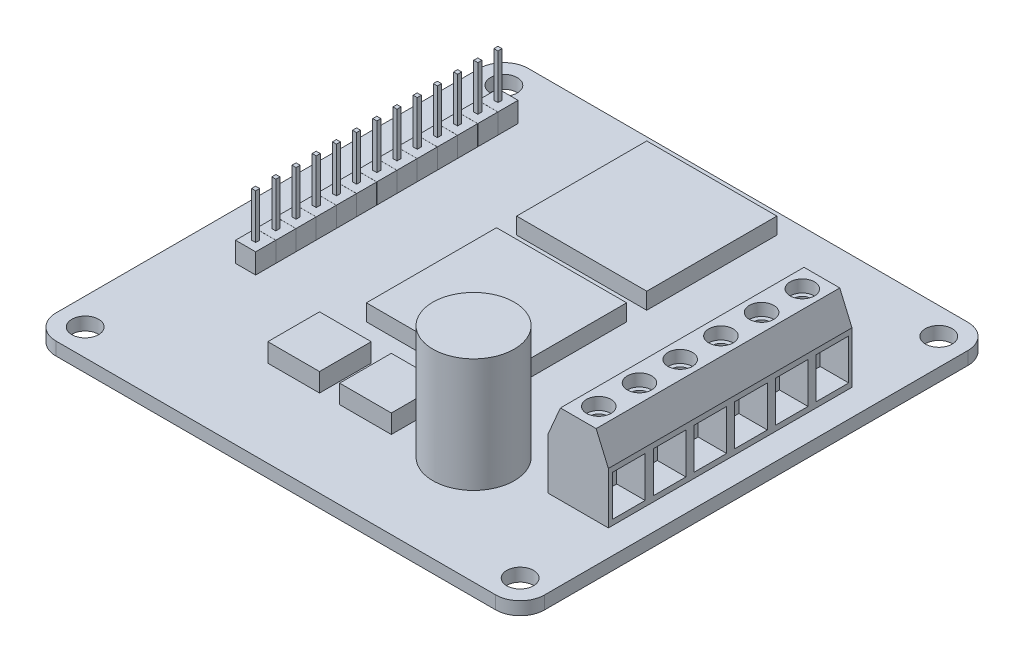
SolidWorks part; units mm, degrees
ref_plane "Front Plane" through (0, 0, 0) normal (0, 0, 1) x (1, 0, 0)
ref_plane "Top Plane" through (0, 0, 0) normal (0, 1, 0) x (1, 0, 0)
ref_plane "Right Plane" through (0, 0, 0) normal (1, 0, 0) x (0, 0, -1)
sketch "Sketch1" plane through (0, 0, 0) normal (0, 1, 0) x (1, 0, 0)
  line L1 (-27, -29) -> (27, -29)
  line L2 (-30, -26) -> (-30, 26)
  line L3 (-27, 29) -> (27, 29)
  line L4 (30, -26) -> (30, 26)
  line L5 (-30, -29) -> (30, 29) construction
  line L6 (-30, 29) -> (30, -29) construction
  arc A0 (-27, -29) -> (-30, -26) centre (-27, -26) cw
  arc A1 (27, -29) -> (30, -26) centre (27, -26) ccw
  arc A2 (27, 29) -> (30, 26) centre (27, 26) cw
  arc A3 (-30, 26) -> (-27, 29) centre (-27, 26) cw
  point P0 (0, 0)
  dimension "D3" = 3
  dimension "D1" = 60
  dimension "D2" = 58
extrude "Boss-Extrude1" add sketch "Sketch1" along normal blind 1.6
sketch "Sketch2" plane through (0, 1.6, 0) normal (0, 1, 0) x (1, 0, 0)
  line L0 (-27, -29) -> (27, -29) construction
  line L1 (30, -26) -> (30, 26) construction
  line L2 (27, 29) -> (-27, 29) construction
  line L3 (-30, 26) -> (-30, -26) construction
  circle A0 centre (-26.71, 25.71) radius 1.645
  circle A1 centre (26.71, 25.71) radius 1.645
  circle A2 centre (-26.71, -25.71) radius 1.645
  circle A3 centre (26.71, -25.71) radius 1.645
  dimension "D1" = 3.29
  dimension "D2" = 3.29
  dimension "D3" = 3.29
  dimension "D4" = 3.29
  dimension "D5" = 3.29
  dimension "D6" = 3.29
  dimension "D7" = 3.29
  dimension "D8" = 3.29
  dimension "D9" = 3.29
  dimension "D10" = 3.29
  dimension "D11" = 3.29
  dimension "D12" = 3.29
extrude "Cut-Extrude1" cut sketch "Sketch2" against normal blind 1.6
sketch "Sketch3" plane through (0, 1.6, 0) normal (0, 1, 0) x (1, 0, 0)
  line L0 (27, 29) -> (-27, 29) construction
  line L1 (-9.9806, 10.55) -> (5.9994, 10.55)
  line L2 (-9.9806, 10.55) -> (-9.9806, 26.53)
  line L3 (-9.9806, 26.53) -> (5.9994, 26.53)
  line L4 (5.9994, 10.55) -> (5.9994, 26.53)
  line L5 (-9.9806, 10.55) -> (5.9994, 26.53) construction
  line L6 (-9.9806, 26.53) -> (5.9994, 10.55) construction
  line L7 (-9.9806, -7.9) -> (5.9994, -7.9)
  line L8 (-9.9806, -7.9) -> (-9.9806, 8.08)
  line L9 (-9.9806, 8.08) -> (5.9994, 8.08)
  line L10 (5.9994, -7.9) -> (5.9994, 8.08)
  line L11 (-9.9806, -7.9) -> (5.9994, 8.08) construction
  line L12 (-9.9806, 8.08) -> (5.9994, -7.9) construction
  point P0 (-1.9906, 18.54)
  point P5 (-1.9906, 0.09)
  dimension "D1" = 15.98
  dimension "D2" = 15.98
  dimension "D3" = 15.98
  dimension "D4" = 15.98
  dimension "D5" = 2.47
  dimension "D6" = 2.47
extrude "Boss-Extrude2" add sketch "Sketch3" along normal blind 2.03
sketch "Sketch4" plane through (0, 1.6, 0) normal (0, 1, 0) x (1, 0, 0)
  line L0 (-9.9806, -7.9) -> (5.9994, -7.9) construction
  line L1 (3.5294, -12) -> (-2.8206, -12)
  line L2 (3.5294, -12) -> (3.5294, -18.35)
  line L3 (3.5294, -18.35) -> (-2.8206, -18.35)
  line L4 (-2.8206, -12) -> (-2.8206, -18.35)
  line L5 (-5.2906, -12) -> (-11.6406, -12)
  line L6 (-5.2906, -12) -> (-5.2906, -18.35)
  line L7 (-5.2906, -18.35) -> (-11.6406, -18.35)
  line L8 (-11.6406, -12) -> (-11.6406, -18.35)
  line L9 (5.9994, -7.9) -> (5.9994, 8.08) construction
  dimension "D1" = 4.1
  dimension "D2" = 2.47
  dimension "D3" = 2.47
  dimension "D4" = 4.1
  dimension "D5" = 6.35
  dimension "D6" = 6.35
  dimension "D7" = 6.35
  dimension "D8" = 6.35
extrude "Boss-Extrude3" add sketch "Sketch4" along normal blind 2.29
sketch "Sketch5" plane through (0, 1.6, 0) normal (0, 1, 0) x (1, 0, 0)
  line L0 (3.5294, -18.35) -> (3.5294, -12) construction
  circle A0 centre (10.9994, -15.7184) radius 5
  dimension "D1" = 10
  dimension "D2" = 7.47
extrude "Boss-Extrude4" add sketch "Sketch5" along normal blind 14
sketch "Sketch6" plane through (0, 1.6, 0) normal (0, 1, 0) x (1, 0, 0)
  line L1 (19.4073, -14.96) -> (26.7973, -14.96)
  line L2 (19.4073, -14.96) -> (19.4073, 14.96)
  line L3 (19.4073, 14.96) -> (26.7973, 14.96)
  line L4 (26.7973, -14.96) -> (26.7973, 14.96)
  line L5 (19.4073, -14.96) -> (26.7973, 14.96) construction
  line L6 (19.4073, 14.96) -> (26.7973, -14.96) construction
  point P0 (23.1023, 0)
  dimension "D1" = 29.92
  dimension "D2" = 7.39
  dimension "D3" = 0
extrude "Boss-Extrude5" add sketch "Sketch6" along normal blind 9.82
sketch "Sketch7" plane through (0, 0, 14.96) normal (0, 0, 1) x (1, 0, 0)
  line L0 (19.4073, 11.42) -> (20.9073, 11.42)
  line L1 (19.4073, 11.42) -> (26.7973, 11.42) construction
  line L2 (20.9073, 11.42) -> (19.4073, 7.9286)
  line L3 (19.4073, 11.42) -> (19.4073, 1.6) construction
  line L4 (19.4073, 7.9286) -> (19.4073, 11.42)
  line L5 (26.7973, 11.42) -> (25.2973, 11.42)
  line L6 (25.2973, 11.42) -> (26.7973, 7.9286)
  line L7 (26.7973, 11.42) -> (26.7973, 1.6) construction
  line L8 (26.7973, 7.9286) -> (26.7973, 11.42)
  dimension "D1" = 1.5
  dimension "D2" = 1.5
  dimension "D3" = 3.8
  dimension "D4" = 3.8
extrude "Cut-Extrude2" cut sketch "Sketch7" against normal blind 29.92
sketch "Sketch8" plane through (0, 11.42, 0) normal (0, 1, 0) x (1, 0, 0)
  line L0 (25.2973, 14.96) -> (25.2973, -14.96) construction
  line L1 (26.7973, 14.96) -> (19.4073, 14.96) construction
  circle A0 centre (23.0973, 12.56) radius 1.5
  circle A1 centre (23.0973, 7.56) radius 1.5
  circle A2 centre (23.0973, 2.56) radius 1.5
  circle A3 centre (23.0973, -2.44) radius 1.5
  circle A4 centre (23.0973, -7.44) radius 1.5
  circle A5 centre (23.0973, -12.44) radius 1.5
  dimension "D1" = 3
  dimension "D2" = 2.2
  dimension "D3" = 2.4
  dimension "D4" = 6
extrude "Cut-Extrude3" cut sketch "Sketch8" against normal blind 1.5
sketch "Sketch9" plane through (0, 1.6, 0) normal (0, 1, 0) x (1, 0, 0)
  line L0 (-30, 26) -> (-30, -26) construction
  line L1 (-24.235, -7.249) -> (-21.765, -7.249)
  line L2 (-24.235, -7.249) -> (-24.235, -9.719)
  line L3 (-24.235, -9.719) -> (-21.765, -9.719)
  line L4 (-21.765, -7.249) -> (-21.765, -9.719)
  line L5 (-24.235, -7.249) -> (-21.765, -9.719) construction
  line L6 (-24.235, -9.719) -> (-21.765, -7.249) construction
  line L7 (-21.765, -4.769) -> (-21.765, -7.239)
  line L8 (-24.235, -4.769) -> (-21.765, -4.769)
  line L9 (-24.235, -4.769) -> (-24.235, -7.239)
  line L10 (-24.235, -7.239) -> (-21.765, -7.239)
  line L11 (-21.765, -2.289) -> (-21.765, -4.759)
  line L12 (-24.235, -2.289) -> (-21.765, -2.289)
  line L13 (-24.235, -2.289) -> (-24.235, -4.759)
  line L14 (-24.235, -4.759) -> (-21.765, -4.759)
  line L15 (-21.765, 0.191) -> (-21.765, -2.279)
  line L16 (-24.235, 0.191) -> (-21.765, 0.191)
  line L17 (-24.235, 0.191) -> (-24.235, -2.279)
  line L18 (-24.235, -2.279) -> (-21.765, -2.279)
  line L19 (-21.765, 2.671) -> (-21.765, 0.201)
  line L20 (-24.235, 2.671) -> (-21.765, 2.671)
  line L21 (-24.235, 2.671) -> (-24.235, 0.201)
  line L22 (-24.235, 0.201) -> (-21.765, 0.201)
  line L23 (-21.765, 5.151) -> (-21.765, 2.681)
  line L24 (-24.235, 5.151) -> (-21.765, 5.151)
  line L25 (-24.235, 5.151) -> (-24.235, 2.681)
  line L26 (-24.235, 2.681) -> (-21.765, 2.681)
  line L27 (-21.765, 7.631) -> (-21.765, 5.161)
  line L28 (-24.235, 7.631) -> (-21.765, 7.631)
  line L29 (-24.235, 7.631) -> (-24.235, 5.161)
  line L30 (-24.235, 5.161) -> (-21.765, 5.161)
  line L31 (-21.765, 10.111) -> (-21.765, 7.641)
  line L32 (-24.235, 10.111) -> (-21.765, 10.111)
  line L33 (-24.235, 10.111) -> (-24.235, 7.641)
  line L34 (-24.235, 7.641) -> (-21.765, 7.641)
  line L35 (-21.765, 12.591) -> (-21.765, 10.121)
  line L36 (-24.235, 12.591) -> (-21.765, 12.591)
  line L37 (-24.235, 12.591) -> (-24.235, 10.121)
  line L38 (-24.235, 10.121) -> (-21.765, 10.121)
  line L39 (-21.765, 15.071) -> (-21.765, 12.601)
  line L40 (-24.235, 15.071) -> (-21.765, 15.071)
  line L41 (-24.235, 15.071) -> (-24.235, 12.601)
  line L42 (-24.235, 12.601) -> (-21.765, 12.601)
  line L43 (-21.765, 17.551) -> (-21.765, 15.081)
  line L44 (-24.235, 17.551) -> (-21.765, 17.551)
  line L45 (-24.235, 17.551) -> (-24.235, 15.081)
  line L46 (-24.235, 15.081) -> (-21.765, 15.081)
  line L47 (-21.765, 20.031) -> (-21.765, 17.561)
  line L48 (-24.235, 20.031) -> (-21.765, 20.031)
  line L49 (-24.235, 20.031) -> (-24.235, 17.561)
  line L50 (-24.235, 17.561) -> (-21.765, 17.561)
  line L51 (-21.765, 22.511) -> (-21.765, 20.041)
  line L52 (-24.235, 22.511) -> (-21.765, 22.511)
  line L53 (-24.235, 22.511) -> (-24.235, 20.041)
  line L54 (-24.235, 20.041) -> (-21.765, 20.041)
  point P0 (-23, -8.484)
  point P9 (-23, -6.004)
  point P14 (-23, -3.524)
  point P19 (-23, -1.044)
  point P24 (-23, 1.436)
  point P29 (-23, 3.916)
  point P34 (-23, 6.396)
  point P39 (-23, 8.876)
  point P44 (-23, 11.356)
  point P49 (-23, 13.836)
  point P54 (-23, 16.316)
  point P59 (-23, 18.796)
  point P64 (-23, 21.276)
  dimension "D1" = 2.47
  dimension "D2" = 2.47
  dimension "D3" = 7
  dimension "D4" = 13
extrude "Boss-Extrude6" add sketch "Sketch9" along normal blind 2.47
sketch "Sketch10" plane through (0, 4.07, 0) normal (0, 1, 0) x (1, 0, 0)
  line L0 (-21.765, -7.249) -> (-24.235, -7.249) construction
  line L1 (-23.25, -8.734) -> (-22.75, -8.734)
  line L2 (-23.25, -8.734) -> (-23.25, -8.234)
  line L3 (-23.25, -8.234) -> (-22.75, -8.234)
  line L4 (-22.75, -8.734) -> (-22.75, -8.234)
  line L5 (-23.25, -8.734) -> (-22.75, -8.234) construction
  line L6 (-23.25, -8.234) -> (-22.75, -8.734) construction
  line L7 (-24.235, -7.249) -> (-24.235, -9.719) construction
  line L8 (-23.25, -5.754) -> (-22.75, -5.754)
  line L9 (-23.25, -6.254) -> (-23.25, -5.754)
  line L10 (-23.25, -6.254) -> (-22.75, -6.254)
  line L11 (-22.75, -6.254) -> (-22.75, -5.754)
  line L12 (-23.25, -3.274) -> (-22.75, -3.274)
  line L13 (-23.25, -3.774) -> (-23.25, -3.274)
  line L14 (-23.25, -3.774) -> (-22.75, -3.774)
  line L15 (-22.75, -3.774) -> (-22.75, -3.274)
  line L16 (-23.25, -0.794) -> (-22.75, -0.794)
  line L17 (-23.25, -1.294) -> (-23.25, -0.794)
  line L18 (-23.25, -1.294) -> (-22.75, -1.294)
  line L19 (-22.75, -1.294) -> (-22.75, -0.794)
  line L20 (-23.25, 1.686) -> (-22.75, 1.686)
  line L21 (-23.25, 1.186) -> (-23.25, 1.686)
  line L22 (-23.25, 1.186) -> (-22.75, 1.186)
  line L23 (-22.75, 1.186) -> (-22.75, 1.686)
  line L24 (-23.25, 4.166) -> (-22.75, 4.166)
  line L25 (-23.25, 3.666) -> (-23.25, 4.166)
  line L26 (-23.25, 3.666) -> (-22.75, 3.666)
  line L27 (-22.75, 3.666) -> (-22.75, 4.166)
  line L28 (-23.25, 6.646) -> (-22.75, 6.646)
  line L29 (-23.25, 6.146) -> (-23.25, 6.646)
  line L30 (-23.25, 6.146) -> (-22.75, 6.146)
  line L31 (-22.75, 6.146) -> (-22.75, 6.646)
  line L32 (-23.25, 9.126) -> (-22.75, 9.126)
  line L33 (-23.25, 8.626) -> (-23.25, 9.126)
  line L34 (-23.25, 8.626) -> (-22.75, 8.626)
  line L35 (-22.75, 8.626) -> (-22.75, 9.126)
  line L36 (-23.25, 11.606) -> (-22.75, 11.606)
  line L37 (-23.25, 11.106) -> (-23.25, 11.606)
  line L38 (-23.25, 11.106) -> (-22.75, 11.106)
  line L39 (-22.75, 11.106) -> (-22.75, 11.606)
  line L40 (-23.25, 14.086) -> (-22.75, 14.086)
  line L41 (-23.25, 13.586) -> (-23.25, 14.086)
  line L42 (-23.25, 13.586) -> (-22.75, 13.586)
  line L43 (-22.75, 13.586) -> (-22.75, 14.086)
  line L44 (-23.25, 16.566) -> (-22.75, 16.566)
  line L45 (-23.25, 16.066) -> (-23.25, 16.566)
  line L46 (-23.25, 16.066) -> (-22.75, 16.066)
  line L47 (-22.75, 16.066) -> (-22.75, 16.566)
  line L48 (-23.25, 19.046) -> (-22.75, 19.046)
  line L49 (-23.25, 18.546) -> (-23.25, 19.046)
  line L50 (-23.25, 18.546) -> (-22.75, 18.546)
  line L51 (-22.75, 18.546) -> (-22.75, 19.046)
  line L52 (-23.25, 21.526) -> (-22.75, 21.526)
  line L53 (-23.25, 21.026) -> (-23.25, 21.526)
  line L54 (-23.25, 21.026) -> (-22.75, 21.026)
  line L55 (-22.75, 21.026) -> (-22.75, 21.526)
  point P0 (-23, -8.484)
  point P7 (-23, -7.249)
  point P12 (-23, -6.004)
  point P17 (-23, -3.524)
  point P22 (-23, -1.044)
  point P27 (-23, 1.436)
  point P32 (-23, 3.916)
  point P37 (-23, 6.396)
  point P42 (-23, 8.876)
  point P47 (-23, 11.356)
  point P52 (-23, 13.836)
  point P57 (-23, 16.316)
  point P62 (-23, 18.796)
  point P67 (-23, 21.276)
  dimension "D1" = 0.5
  dimension "D2" = 0.5
  dimension "D3" = 1.235
  dimension "D4" = 1.235
  dimension "D5" = 13
extrude "Boss-Extrude7" add sketch "Sketch10" along normal blind 5.5
sketch "Sketch11" plane through (26.7973, 0, 0) normal (1, 0, 0) x (0, 0, -1)
  line L0 (14.96, 4.7643) -> (-14.96, 4.7643) construction
  line L1 (14.96, 7.9286) -> (14.96, 1.6) construction
  line L2 (-14.96, 7.9286) -> (-14.96, 1.6) construction
  line L3 (5.56, 7.2643) -> (9.56, 7.2643)
  line L4 (10.56, 2.2643) -> (14.56, 2.2643)
  line L5 (10.56, 2.2643) -> (10.56, 7.2643)
  line L6 (10.56, 7.2643) -> (14.56, 7.2643)
  line L7 (14.56, 2.2643) -> (14.56, 7.2643)
  line L8 (10.56, 2.2643) -> (14.56, 7.2643) construction
  line L9 (10.56, 7.2643) -> (14.56, 2.2643) construction
  line L10 (5.56, 2.2643) -> (5.56, 7.2643)
  line L11 (5.56, 2.2643) -> (9.56, 2.2643)
  line L12 (9.56, 2.2643) -> (9.56, 7.2643)
  line L13 (0.56, 7.2643) -> (4.56, 7.2643)
  line L14 (0.56, 2.2643) -> (0.56, 7.2643)
  line L15 (0.56, 2.2643) -> (4.56, 2.2643)
  line L16 (4.56, 2.2643) -> (4.56, 7.2643)
  line L17 (-4.44, 7.2643) -> (-0.44, 7.2643)
  line L18 (-4.44, 2.2643) -> (-4.44, 7.2643)
  line L19 (-4.44, 2.2643) -> (-0.44, 2.2643)
  line L20 (-0.44, 2.2643) -> (-0.44, 7.2643)
  line L21 (-9.44, 7.2643) -> (-5.44, 7.2643)
  line L22 (-9.44, 2.2643) -> (-9.44, 7.2643)
  line L23 (-9.44, 2.2643) -> (-5.44, 2.2643)
  line L24 (-5.44, 2.2643) -> (-5.44, 7.2643)
  line L25 (-14.44, 7.2643) -> (-10.44, 7.2643)
  line L26 (-14.44, 2.2643) -> (-14.44, 7.2643)
  line L27 (-14.44, 2.2643) -> (-10.44, 2.2643)
  line L28 (-10.44, 2.2643) -> (-10.44, 7.2643)
  point P6 (12.56, 4.7643)
  point P11 (7.56, 4.7643)
  point P17 (2.56, 4.7643)
  point P22 (-2.44, 4.7643)
  point P27 (-7.44, 4.7643)
  point P32 (-12.44, 4.7643)
  dimension "D1" = 2.4
  dimension "D2" = 4
  dimension "D3" = 5
  dimension "D4" = 6
extrude "Cut-Extrude4" cut sketch "Sketch11" against normal blind 3.5
sketch "Sketch12" plane through (0, 9.92, 0) normal (0, 1, 0) x (1, 0, 0)
  circle A0 centre (23.0973, -12.44) radius 1
  circle A1 centre (23.0973, -7.44) radius 1
  circle A2 centre (23.0973, -2.44) radius 1
  circle A3 centre (23.0973, 2.56) radius 1
  circle A4 centre (23.0973, 7.56) radius 1
  circle A5 centre (23.0973, 12.56) radius 1
  dimension "D1" = 2
  dimension "D2" = 6
extrude "Cut-Extrude5" cut sketch "Sketch12" against normal blind 9.8
